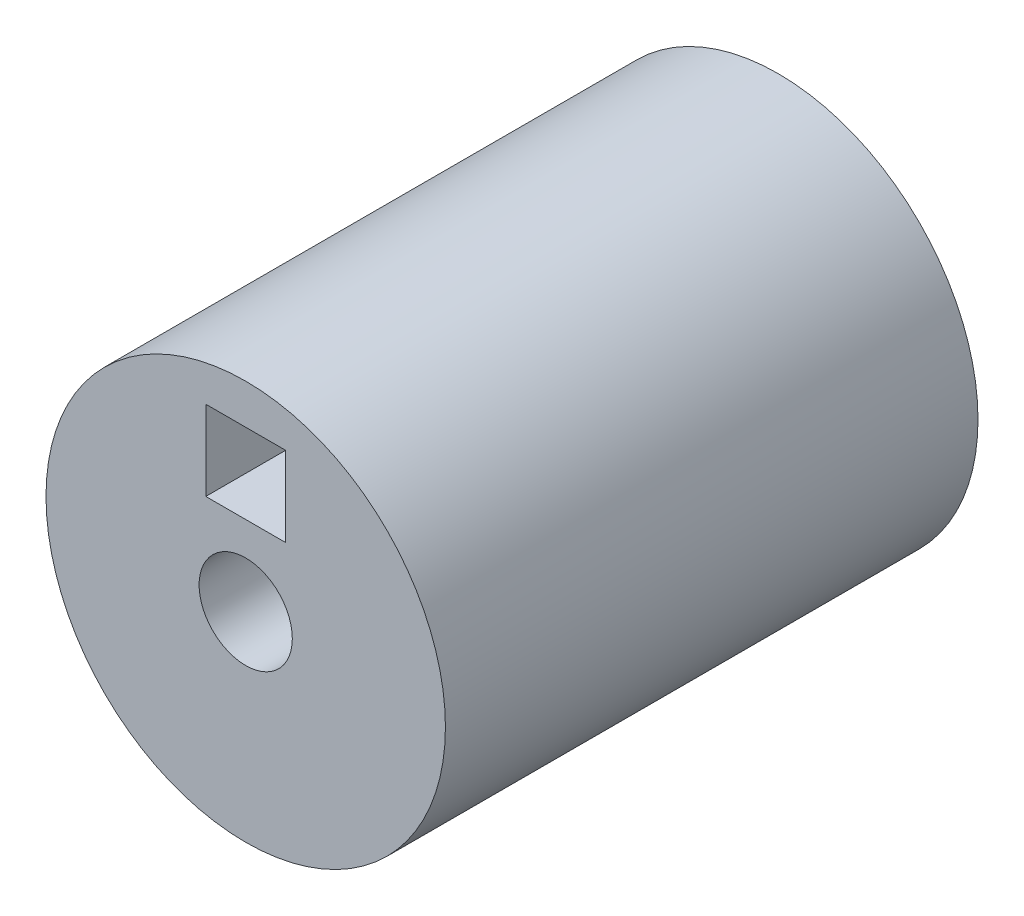
SolidWorks part; units mm, degrees
ref_plane "Front Plane" through (0, 0, 0) normal (0, 0, 1) x (1, 0, 0)
ref_plane "Top Plane" through (0, 0, 0) normal (0, 1, 0) x (1, 0, 0)
ref_plane "Right Plane" through (0, 0, 0) normal (1, 0, 0) x (0, 0, -1)
sketch "Sketch1" plane through (0, 0, 0) normal (0, 0, 1) x (1, 0, 0)
  circle A0 centre (0, 0) radius 7.5
  circle A1 centre (0, 0) radius 1.75
  circle A2 centre (0, 0) radius 4.5 construction
  dimension "D1" = 15
  dimension "D2" = 3.5
  dimension "D3" = 9
extrude "Boss-Extrude1" add sketch "Sketch1" along normal blind 20
sketch "Sketch2" plane through (0, 0, 20) normal (0, 0, 1) x (1, 0, 0)
  line L1 (-1.5, 3) -> (1.5, 3)
  line L2 (-1.5, 3) -> (-1.5, 6)
  line L3 (-1.5, 6) -> (1.5, 6)
  line L4 (1.5, 3) -> (1.5, 6)
  line L5 (-1.5, 3) -> (1.5, 6) construction
  line L6 (-1.5, 6) -> (1.5, 3) construction
  circle A0 centre (0, 0) radius 4.5 construction
  point P3 (0, 4.5)
  dimension "D1" = 9
  dimension "D2" = 3
extrude "Cut-Extrude1" cut sketch "Sketch2" against normal blind 8
sketch "Sketch3" plane through (0, 0, 0) normal (0, 0, -1) x (-1, 0, 0)
  line L0 (0, 0) -> (0, 4.5) construction
  line L1 (0, 0) -> (1.3906, 4.2798) construction
  line L2 (3.2807, 5.2428) -> (-0.4995, 3.3167) construction
  line L3 (2.3536, 2.3896) -> (0.4275, 6.1699) construction
  line L4 (-0.4995, 3.3167) -> (0.4275, 6.1699)
  line L5 (0.4275, 6.1699) -> (3.2807, 5.2428)
  line L6 (3.2807, 5.2428) -> (2.3536, 2.3896)
  line L7 (2.3536, 2.3896) -> (-0.4995, 3.3167)
  circle A0 centre (0, 0) radius 4.5 construction
  point P9 (1.3906, 4.2798)
  point P10 (1.3906, 4.2798)
  dimension "D1" = 9
  dimension "D2" = 18
  dimension "D3" = 3
extrude "Cut-Extrude2" cut sketch "Sketch3" against normal blind 8
